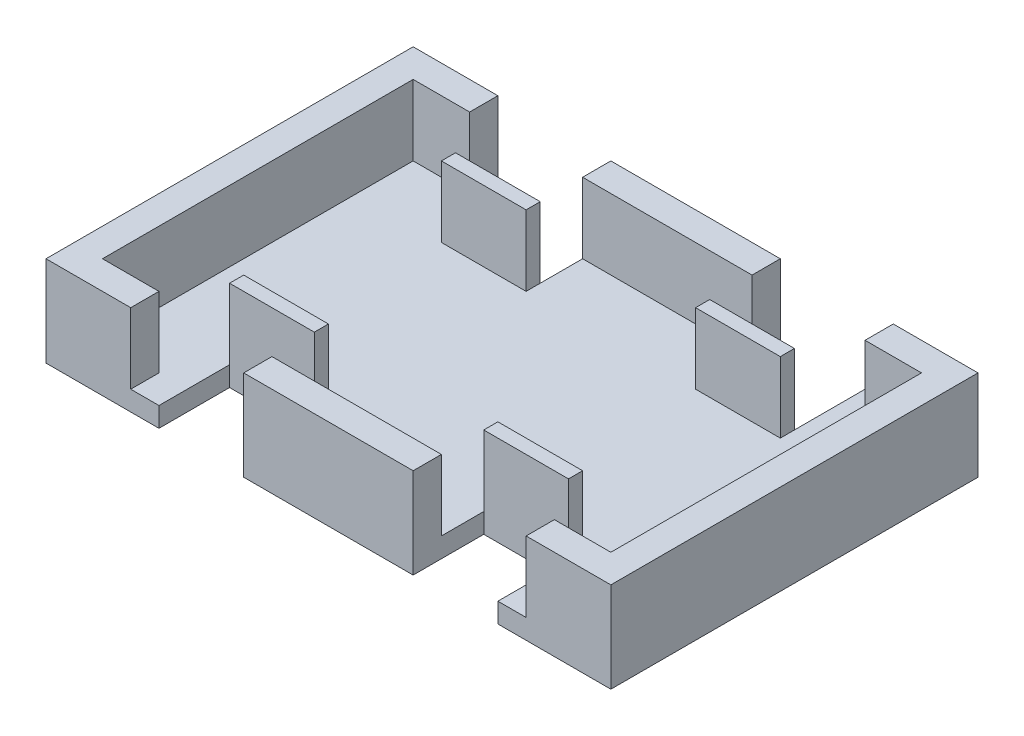
SolidWorks part; units mm, degrees
material "ABS"
ref_plane "前基準面" through (0, 0, 0) normal (0, 0, 1) x (1, 0, 0)
ref_plane "上基準面" through (0, 0, 0) normal (0, 1, 0) x (1, 0, 0)
ref_plane "右基準面" through (0, 0, 0) normal (1, 0, 0) x (0, 0, -1)
sketch "草圖1" plane through (0, 0, 0) normal (0, 1, 0) x (1, 0, 0)
  line L0 (-60, 65) -> (-60, 40)
  line L1 (-100, -65) -> (-60, -65)
  line L2 (-100, -65) -> (-100, 65)
  line L3 (-100, 65) -> (-60, 65)
  line L4 (100, -65) -> (100, 65)
  line L5 (-100, -65) -> (100, 65) construction
  line L6 (-100, 65) -> (100, -65) construction
  line L7 (-60, 40) -> (-30, 40)
  line L8 (-30, 40) -> (-30, 65)
  line L9 (-1000, 0) -> (49000, 0) construction
  line L10 (0, -1000) -> (0, 49000) construction
  line L11 (60, 40) -> (30, 40)
  line L12 (30, 40) -> (30, 65)
  line L13 (60, 65) -> (60, 40)
  line L14 (60, -40) -> (30, -40)
  line L15 (60, -65) -> (60, -40)
  line L16 (30, -40) -> (30, -65)
  line L17 (-60, -40) -> (-30, -40)
  line L18 (-30, -40) -> (-30, -65)
  line L19 (-60, -65) -> (-60, -40)
  line L20 (-30, 65) -> (30, 65)
  line L21 (-30, -65) -> (30, -65)
  line L22 (60, -65) -> (100, -65)
  line L23 (60, 65) -> (100, 65)
  point P0 (0, 0)
  dimension "D1" = 200
  dimension "D2" = 130
  dimension "D3" = 40
  dimension "D4" = 30
  dimension "D5" = 25
extrude "填料-伸長1" add sketch "草圖1" along normal blind 5 and the other way blind 2
sketch "草圖2" plane through (0, 5, 0) normal (0, 1, 0) x (1, 0, 0)
  line L0 (0, -1000) -> (0, 49000) construction
  line L1 (-1000, 0) -> (49000, 0) construction
  line L2 (-60, 40) -> (-60, 35)
  line L3 (-60, 40) -> (-30, 40)
  line L4 (-30, 40) -> (-30, 35)
  line L5 (-30, 35) -> (-60, 35)
  line L6 (-30, -40) -> (-30, -35)
  line L7 (-30, -35) -> (-60, -35)
  line L8 (-60, -40) -> (-60, -35)
  line L9 (-60, -40) -> (-30, -40)
  line L10 (60, -40) -> (30, -40)
  line L11 (60, -40) -> (60, -35)
  line L12 (30, -35) -> (60, -35)
  line L13 (30, -40) -> (30, -35)
  line L14 (30, 40) -> (30, 35)
  line L15 (60, 40) -> (30, 40)
  line L16 (60, 40) -> (60, 35)
  line L17 (30, 35) -> (60, 35)
  dimension "D1" = 5
extrude "填料-伸長2" add sketch "草圖2" along normal blind 25
sketch "草圖3" plane through (0, 5, 0) normal (0, 1, 0) x (1, 0, 0)
  line L0 (-1000, 0) -> (-100, 0) construction
  line L9 (0, -1000) -> (0, 49000) construction
  line L10 (100, -65) -> (70, -65)
  line L11 (70, -65) -> (70, -55)
  line L12 (70, -55) -> (90, -55)
  line L13 (90, 0) -> (90, -55)
  line L15 (100, -65) -> (100, 0)
  line L16 (100, 65) -> (100, 0)
  line L18 (90, 0) -> (90, 55)
  line L19 (70, 55) -> (90, 55)
  line L20 (70, 65) -> (70, 55)
  line L21 (100, 65) -> (70, 65)
  line L28 (30, 65) -> (-30, 65) construction
  line L29 (-30, 65) -> (30, 65)
  line L30 (-30, 65) -> (-30, 55)
  line L31 (-30, 55) -> (30, 55)
  line L32 (30, 65) -> (30, 55)
  line L33 (-30, -65) -> (-30, -55)
  line L34 (-30, -55) -> (30, -55)
  line L35 (30, -65) -> (30, -55)
  line L36 (-30, -65) -> (30, -65)
  line L37 (-90, 0) -> (90, 0) construction
  line L38 (100, 0) -> (49000, 0) construction
  line L39 (-100, -65) -> (-100, 0)
  line L40 (-100, -65) -> (-70, -65)
  line L41 (-70, -65) -> (-70, -55)
  line L42 (-70, -55) -> (-90, -55)
  line L43 (-90, 0) -> (-90, -55)
  line L44 (-90, 0) -> (-90, 55)
  line L45 (-70, 55) -> (-90, 55)
  line L46 (-70, 65) -> (-70, 55)
  line L47 (-100, 65) -> (-70, 65)
  line L48 (-100, 65) -> (-100, 0)
  dimension "D1" = 65
  dimension "D3" = 10
  dimension "D4" = 60
  dimension "D6" = 30
sketch "草圖4" plane through (0, 5, 0) normal (0, 1, 0) x (1, 0, 0)
  line L0 (-1000, 0) -> (49000, 0) construction
  line L1 (60, 65) -> (52.3905, 65)
  line L2 (60, 65) -> (60, 50)
  line L3 (60, 50) -> (52.3905, 50)
  line L4 (52.3905, 65) -> (52.3905, 50)
  line L5 (0, -1000) -> (0, 49000) construction
  line L6 (60, -50) -> (52.3905, -50)
  line L7 (60, -65) -> (52.3905, -65)
  line L8 (60, -65) -> (60, -50)
  line L9 (52.3905, -65) -> (52.3905, -50)
  line L10 (-60, -65) -> (-52.3905, -65)
  line L11 (-52.3905, -65) -> (-52.3905, -50)
  line L12 (-60, -65) -> (-60, -50)
  line L13 (-60, -50) -> (-52.3905, -50)
  line L14 (-60, 50) -> (-52.3905, 50)
  line L15 (-60, 65) -> (-60, 50)
  line L16 (-60, 65) -> (-52.3905, 65)
  line L17 (-52.3905, 65) -> (-52.3905, 50)
  dimension "D1" = 15
extrude "除料-伸長2" [suppressed] cut sketch "草圖4" against normal blind 5
sketch "草圖5" plane through (60, 0, 0) normal (-1, 0, 0) x (0, 0, 1)
  line L1 (0, -1000) -> (0, 1000) construction
  line L2 (65, -2) -> (-65, -2) construction
  circle A0 centre (-65.983, 1.5) radius 2
  circle A1 centre (65.983, 1.5) radius 2
  point P10 (0, -2)
  point P15 (0, 0)
  point P17 (0, 0)
  dimension "D1" = 4
  dimension "D3" = 1.5
  dimension "D2" = 66
extrude "除料-伸長3" [suppressed] cut sketch "草圖5" against normal blind 8
mirror "鏡射1" [suppressed] about plane through (0, 0, 0) normal (1, 0, 0)
extrude "填料-伸長3" add sketch "草圖3" along normal blind 25
sketch "草圖6" [suppressed] plane through (0, 5, 0) normal (0, 1, 0) x (1, 0, 0)
  line L0 (-1000, 0) -> (49000, 0) construction
  line L1 (-85, 30) -> (-47.5, 30)
  line L2 (-85, 30) -> (-85, 5)
  line L3 (-85, 5) -> (-47.5, 5)
  line L4 (-47.5, 30) -> (-47.5, 5)
  line L5 (-85, -5) -> (-47.5, -5)
  line L6 (-85, -5) -> (-85, -30)
  line L7 (-85, -30) -> (-47.5, -30)
  line L8 (-47.5, -5) -> (-47.5, -30)
  line L9 (47.5, 30) -> (85, 30)
  line L10 (47.5, 30) -> (47.5, 5)
  line L11 (47.5, 5) -> (85, 5)
  line L12 (85, 30) -> (85, 5)
  line L13 (47.5, -5) -> (85, -5)
  line L14 (47.5, -5) -> (47.5, -30)
  line L15 (47.5, -30) -> (85, -30)
  line L16 (85, -5) -> (85, -30)
  line L17 (-42.5, -5) -> (-5, -5)
  line L18 (-42.5, -5) -> (-42.5, -30)
  line L19 (-42.5, -30) -> (-5, -30)
  line L20 (-5, -5) -> (-5, -30)
  line L21 (5, -5) -> (42.5, -5)
  line L22 (5, -5) -> (5, -30)
  line L23 (5, -30) -> (42.5, -30)
  line L24 (42.5, -5) -> (42.5, -30)
  line L25 (-42.5, 30) -> (-5, 30)
  line L26 (-42.5, 30) -> (-42.5, 5)
  line L27 (-42.5, 5) -> (-5, 5)
  line L28 (-5, 30) -> (-5, 5)
  line L29 (5, 30) -> (42.5, 30)
  line L30 (5, 30) -> (5, 5)
  line L31 (5, 5) -> (42.5, 5)
  line L32 (42.5, 30) -> (42.5, 5)
  line L33 (-90, 40) -> (-90, -40) construction
  line L34 (0, -1000) -> (0, 49000) construction
  dimension "D1" = 37.5
  dimension "D2" = 25
  dimension "D3" = 5
  dimension "D4" = 5
  dimension "D5" = 5
  dimension "D6" = 10
extrude "除料-伸長4" [suppressed] cut sketch "草圖6" against normal through all
